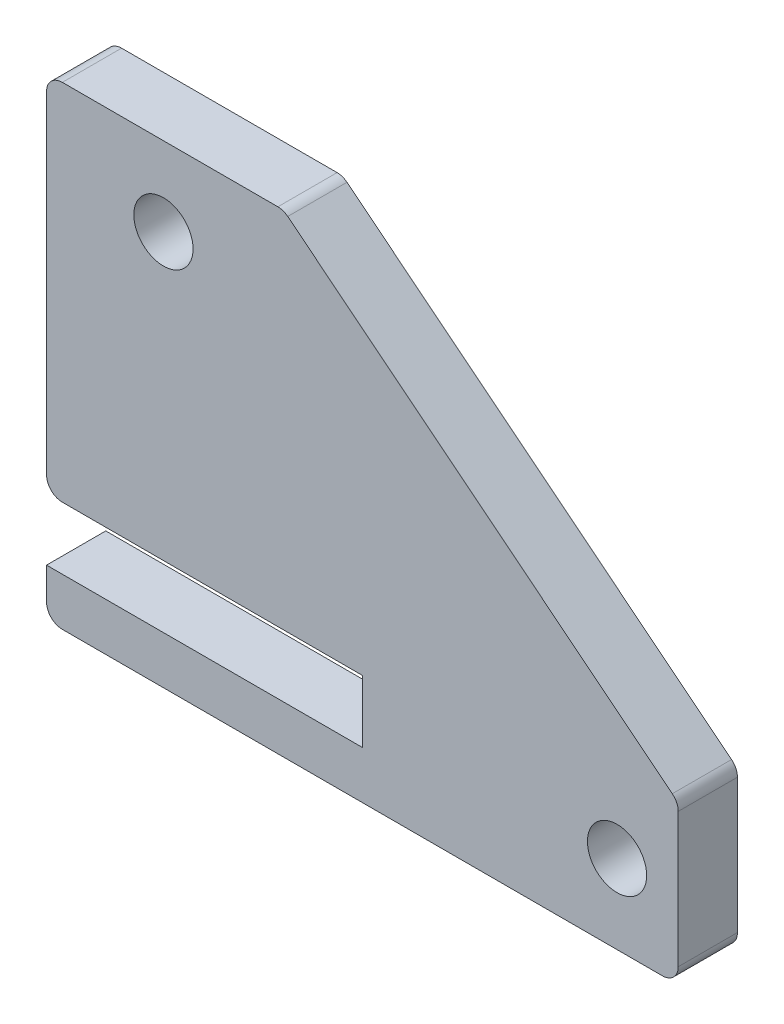
SolidWorks part; units mm, degrees
material "Corrugated Paper"
ref_plane "Front Plane" through (0, 0, 0) normal (0, 0, 1) x (1, 0, 0)
ref_plane "Top Plane" through (0, 0, 0) normal (0, 1, 0) x (1, 0, 0)
ref_plane "Right Plane" through (0, 0, 0) normal (1, 0, 0) x (0, 0, -1)
sketch "Sketch1" plane through (0, 0, 0) normal (0, 0, 1) x (1, 0, 0)
  line L0 (-25.4, 2.5082) -> (-25.4, 6.35)
  line L1 (-25.4, -2.5082) -> (0, -2.5082)
  line L3 (-25.4, 2.5082) -> (0, 2.5082)
  line L4 (0, -2.5082) -> (0, 2.5082)
  line L5 (-25.4, 6.35) -> (25.4, 6.35)
  line L6 (0, 0) -> (25.4, 0) construction
  line L7 (25.4, 6.35) -> (25.4, -6.35)
  line L8 (-25.4, -6.35) -> (25.4, -6.35)
  line L9 (-25.4, -2.5082) -> (-25.4, -6.35)
  line L11 (-25.4, 6.35) -> (25.4, 6.35)
  line L12 (-25.4, 6.35) -> (-25.4, 31.75)
  line L13 (-25.4, 31.75) -> (25.4, 31.75)
  line L14 (25.4, 6.35) -> (25.4, 31.75)
  dimension "D1" = 25.4
  dimension "D2" = 5.0165
  dimension "D3" = 25.4
  dimension "D4" = 12.7
  dimension "D5" = 38.1
extrude "Boss-Extrude1" add sketch "Sketch1" along normal mid plane 4.7625 contours L5 L14 L13 L12 | L6 L4 L1 L9 L8 L7 | L4 L6 L7 L5 L0 L3
sketch "Sketch2" plane through (0, 0, 2.3813) normal (0, 0, 1) x (1, 0, 0)
  line L0 (0, 0) -> (25.4, 0) construction
  line L2 (25.4, -6.35) -> (25.4, 31.75) construction
  circle A0 centre (20.4787, 0) radius 2.3813
  dimension "D1" = 4.7625
  dimension "D2" = 2.54
extrude "Cut-Extrude1" cut sketch "Sketch2" against normal through all
sketch "Sketch3" plane through (0, 0, 2.3813) normal (0, 0, 1) x (1, 0, 0)
  circle A0 centre (-15.9992, 25.4) radius 2.3813
  circle A1 centre (20.4787, 0) radius 2.3813 construction
  dimension "D1" = 44.45
  dimension "D2" = 25.4
extrude "Cut-Extrude2" cut sketch "Sketch3" against normal through all
sketch "Sketch4" plane through (0, 0, 2.3813) normal (0, 0, 1) x (1, 0, 0)
  line L0 (-6.35, 31.75) -> (25.4, 6.35)
  line L1 (-25.4, 31.75) -> (25.4, 31.75) construction
  line L2 (25.4, -6.35) -> (25.4, 31.75) construction
  line L3 (-6.35, 31.75) -> (25.4, 31.75)
  line L4 (25.4, 31.75) -> (25.4, 6.35)
  dimension "D1" = 25.4
  dimension "D2" = 31.75
extrude "Cut-Extrude3" cut sketch "Sketch4" against normal through all
fillet "Fillet1" radius 1.27 6 edges at (-25.4, -6.35, 0) (25.4, -6.35, 0) (-25.4, 2.5082, 0) (-25.4, 31.75, 0) (25.4, 6.35, 0) (-6.35, 31.75, 0)
equation "\"D2@Sketch1\"=\"thick\"+\"clear\""
equation "\"D1@Sketch2\" = \"rodThick\""
equation "\"D1@Boss-Extrude1\" = \"thick\""
equation "\"rodThick\"= 3/16in"
equation "\"thick\"= 3/16in"
equation "\"clear\"= 0.01in"
